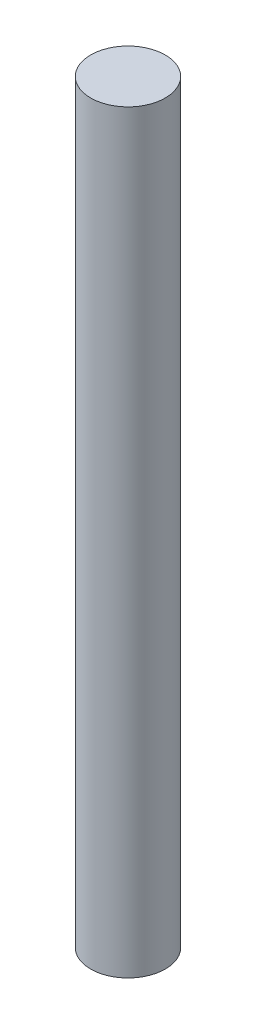
SolidWorks part; units mm, degrees
ref_plane "Alzado" through (0, 0, 0) normal (0, 0, 1) x (1, 0, 0)
ref_plane "Planta" through (0, 0, 0) normal (0, 1, 0) x (1, 0, 0)
ref_plane "Vista lateral" through (0, 0, 0) normal (1, 0, 0) x (0, 0, -1)
sketch "Croquis1" plane through (0, 0, 0) normal (0, 1, 0) x (1, 0, 0)
  circle A0 centre (0, 0) radius 4
  dimension "D1" = 8
extrude "Saliente-Extruir1" add sketch "Croquis1" along normal blind 80.9
sketch "Croquis2" plane through (0, 80.9, 0) normal (0, 1, 0) x (1, 0, 0)
  circle A0 centre (0, 0) radius 2.3813
  dimension "D1" = 4.7625
ref_plane "Plano1" through (0, 34.075, 0) normal (0, 1, 0) x (1, 0, 0)
